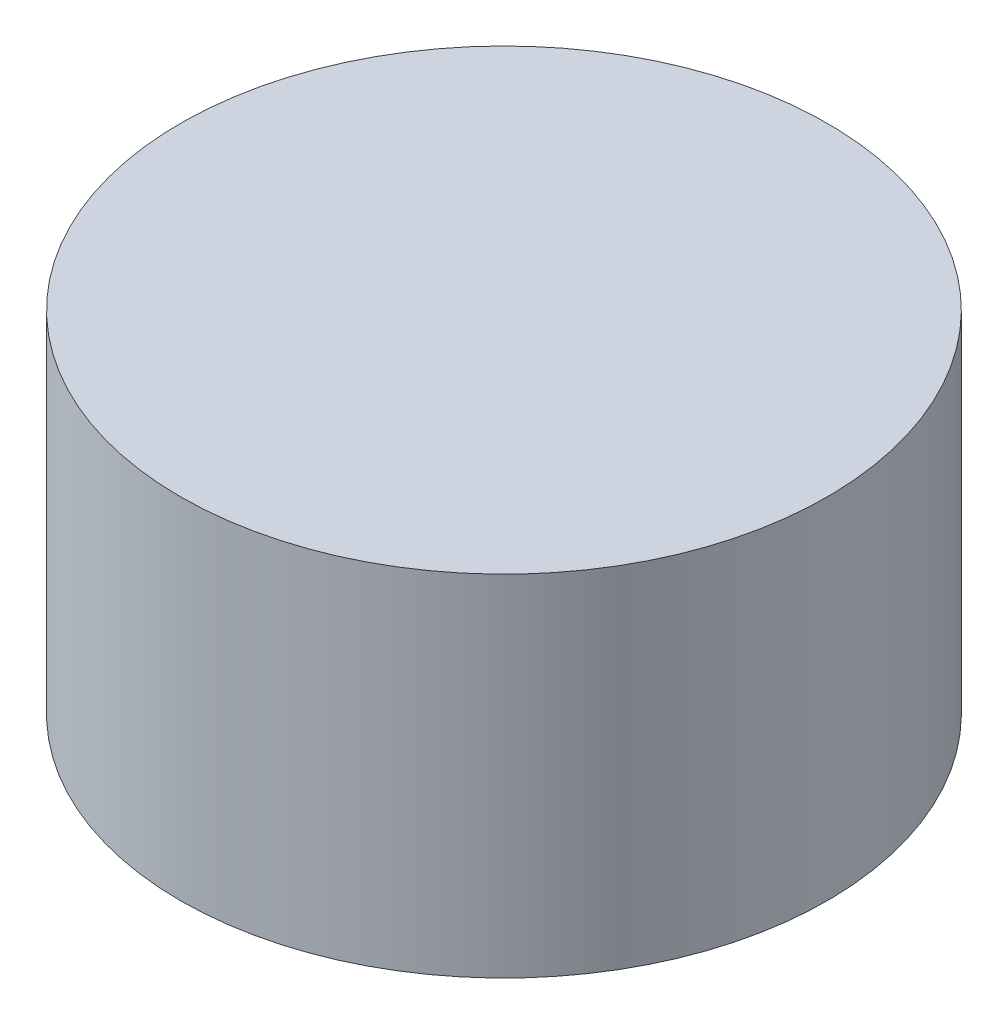
SolidWorks part; units mm, degrees
ref_plane "Front Plane" through (0, 0, 0) normal (0, 0, 1) x (1, 0, 0)
ref_plane "Top Plane" through (0, 0, 0) normal (0, 1, 0) x (1, 0, 0)
ref_plane "Right Plane" through (0, 0, 0) normal (1, 0, 0) x (0, 0, -1)
sketch "Sketch2" plane through (0, 0, 0) normal (0, 1, 0) x (1, 0, 0)
  circle A0 centre (0, 0) radius 1.7145
  dimension "D1" = 3.429
extrude "Boss-Extrude1" add sketch "Sketch2" along normal blind 1.8542
